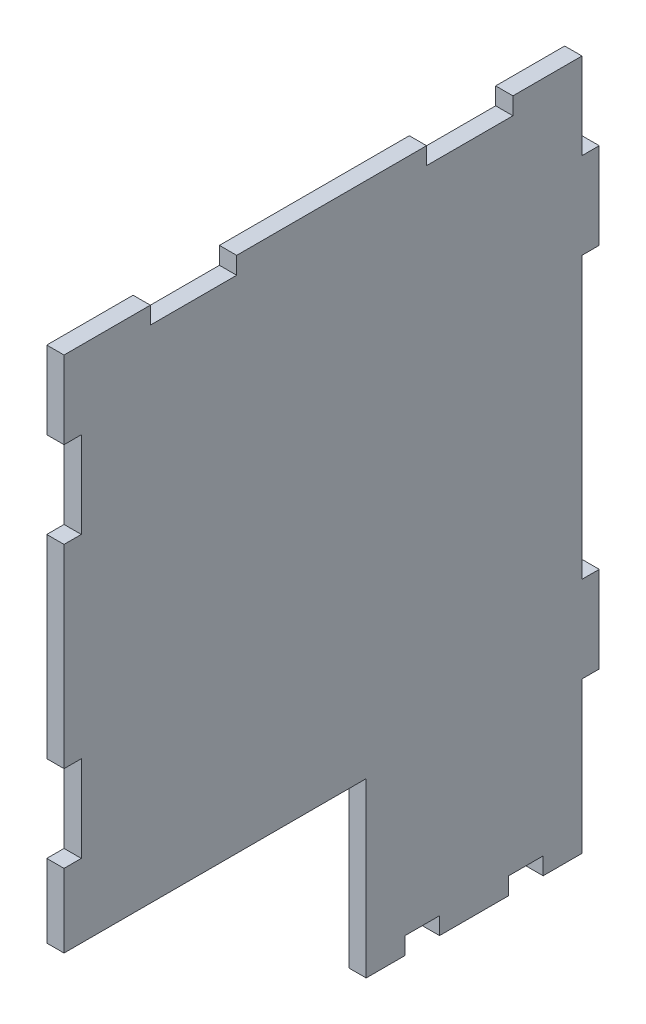
SolidWorks part; units mm, degrees
ref_plane "Front Plane" through (0, 0, 0) normal (0, 0, 1) x (1, 0, 0)
ref_plane "Top Plane" through (0, 0, 0) normal (0, 1, 0) x (1, 0, 0)
ref_plane "Right Plane" through (0, 0, 0) normal (1, 0, 0) x (0, 0, -1)
sketch "Sketch1" plane through (0, 0, 0) normal (0, 0, 1) x (1, 0, 0)
  line L0 (-101.6, -101.6) -> (101.6, -101.6) construction
  line L1 (-101.6, 101.6) -> (-96.52, 101.6)
  line L2 (-101.6, 101.6) -> (-101.6, -101.6)
  line L3 (-101.6, -101.6) -> (-96.52, -101.6)
  line L4 (-96.52, 101.6) -> (-96.52, -101.6)
  dimension "D1" = 5.08
extrude "Boss-Extrude1" add sketch "Sketch1" along normal blind 152.4
sketch "Sketch2" plane through (-101.6, 0, 0) normal (-1, 0, 0) x (0, 0, 1)
  line L0 (0, 101.6) -> (0, -101.6) construction
  line L1 (152.4, -101.6) -> (63.5, -101.6)
  line L2 (152.4, -101.6) -> (152.4, -50.8)
  line L3 (152.4, -50.8) -> (63.5, -50.8)
  line L4 (63.5, -101.6) -> (63.5, -50.8)
  dimension "D1" = 50.8
  dimension "D2" = 63.5
extrude "Cut-Extrude1" cut sketch "Sketch2" against normal blind 5.08
sketch "Sketch3" plane through (0, -101.6, 0) normal (0, -1, 0) x (1, 0, 0)
  line L0 (-101.6, 63.5) -> (-101.6, 0) construction
  line L1 (-101.6, 52.07) -> (-96.52, 52.07)
  line L2 (-101.6, 52.07) -> (-101.6, 41.91)
  line L3 (-101.6, 41.91) -> (-96.52, 41.91)
  line L4 (-96.52, 52.07) -> (-96.52, 41.91)
  line L5 (-96.52, 63.5) -> (-96.52, 0) construction
  line L6 (-96.52, 63.5) -> (-96.52, 52.07)
  line L7 (-101.6, 21.59) -> (-96.52, 21.59)
  line L8 (-101.6, 21.59) -> (-101.6, 11.43)
  line L9 (-101.6, 11.43) -> (-96.52, 11.43)
  line L10 (-96.52, 21.59) -> (-96.52, 11.43)
  line L11 (-96.52, 0) -> (-96.52, 11.43)
  line M11 (-96.52, 0) -> (-96.52, 63.5)
  line M13 (-101.6, 63.5) -> (-101.6, 0)
  dimension "D1" = 10.16
  dimension "D2" = 11.43
extrude "Cut-Extrude2" cut sketch "Sketch3" against normal blind 5.08 contours L3 L1 M13 M11 | L9 L7 M13 M11
sketch "Sketch5" plane through (0, 0, 0) normal (0, 0, -1) x (-1, 0, 0)
  line L0 (96.52, -101.6) -> (96.52, 101.6) construction
  line L1 (96.52, -57.15) -> (101.6, -57.15)
  line L2 (96.52, -57.15) -> (96.52, -31.75)
  line L3 (96.52, -31.75) -> (101.6, -31.75)
  line L4 (101.6, -57.15) -> (101.6, -31.75)
  line L5 (96.52, -57.15) -> (101.6, -57.15) construction
  line L6 (101.6, 101.6) -> (101.6, -101.6) construction
  line L7 (96.52, 50.8) -> (101.6, 50.8) construction
  line L8 (101.6, 50.8) -> (96.52, 50.8)
  line L9 (101.6, 50.8) -> (101.6, 76.2)
  line L10 (101.6, 76.2) -> (96.52, 76.2)
  line L11 (96.52, 50.8) -> (96.52, 76.2)
  dimension "D1" = 25.4
  dimension "D2" = 25.4
extrude "Boss-Extrude2" add sketch "Sketch5" along normal blind 5.08 contours L2 L1 L4 L3 | L9 L8 L11 L10
sketch "Sketch6" plane through (-96.52, 0, 0) normal (1, 0, 0) x (0, 0, -1)
  line L0 (-152.4, 101.6) -> (0, 101.6) construction
  line L1 (-127, 101.6) -> (-101.6, 101.6)
  line L2 (-127, 101.6) -> (-127, 96.52)
  line L3 (-127, 96.52) -> (-101.6, 96.52)
  line L4 (-101.6, 101.6) -> (-101.6, 96.52)
  line L5 (-152.4, -50.8) -> (-152.4, 101.6) construction
  line L6 (-45.72, 101.6) -> (-20.32, 101.6)
  line L7 (-45.72, 101.6) -> (-45.72, 96.52)
  line L8 (-45.72, 96.52) -> (-20.32, 96.52)
  line L9 (-20.32, 101.6) -> (-20.32, 96.52)
  line L10 (-152.4, 78.74) -> (-147.32, 78.74)
  line L11 (-152.4, 78.74) -> (-152.4, 53.34)
  line L12 (-152.4, 53.34) -> (-147.32, 53.34)
  line L13 (-147.32, 78.74) -> (-147.32, 53.34)
  line L14 (-152.4, -50.8) -> (-63.5, -50.8) construction
  line L15 (-152.4, -29.21) -> (-147.32, -29.21)
  line L16 (-152.4, -29.21) -> (-152.4, -3.81)
  line L17 (-152.4, -3.81) -> (-147.32, -3.81)
  line L18 (-147.32, -29.21) -> (-147.32, -3.81)
  line L19 (5.08, 101.6) -> (5.08, 76.2) construction
  dimension "D1" = 5.08
  dimension "D2" = 25.4
  dimension "D3" = 21.59
  dimension "D4" = 22.86
  dimension "D5" = 25.4
  dimension "D6" = 25.4
extrude "Cut-Extrude3" cut sketch "Sketch6" against normal blind 5.08
